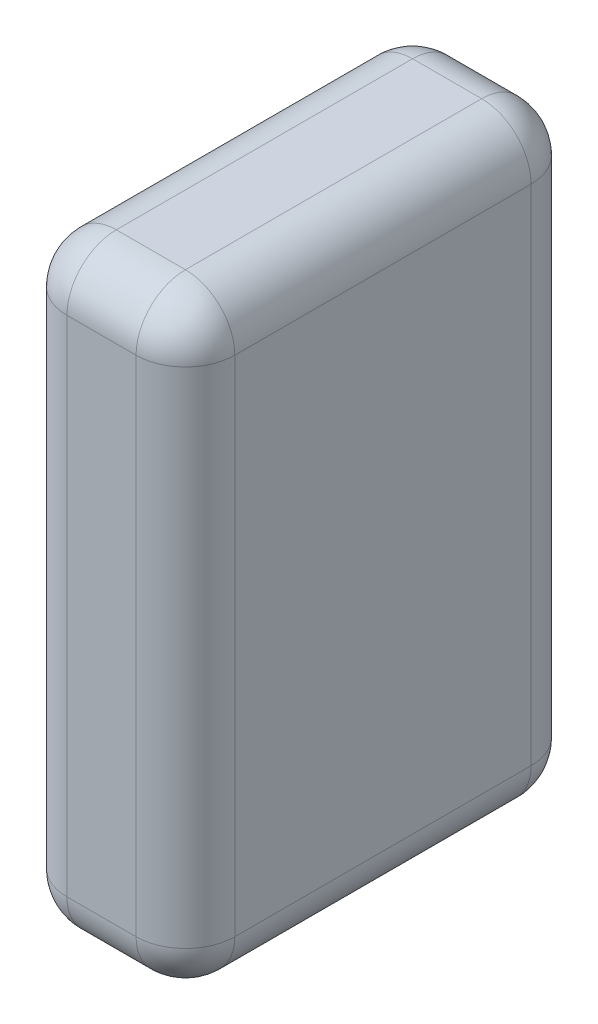
SolidWorks part; units mm, degrees
ref_plane "Front Plane" through (0, 0, 0) normal (0, 0, 1) x (1, 0, 0)
ref_plane "Top Plane" through (0, 0, 0) normal (0, 1, 0) x (1, 0, 0)
ref_plane "Right Plane" through (0, 0, 0) normal (1, 0, 0) x (0, 0, -1)
sketch "xy" plane through (0, 0, 0) normal (0, 0, 1) x (1, 0, 0)
  line L0 (0, 18.1755) -> (0, -18.1755) construction
  line L1 (-29.7176, 0) -> (29.7176, 0) construction
sketch "z" plane through (0, 0, 0) normal (1, 0, 0) x (0, 0, -1)
  line L0 (-17.0064, 0) -> (17.0064, 0) construction
sketch "FrontSketch" plane through (0, 0, 0) normal (0, 0, 1) x (1, 0, 0)
  line L1 (8.5, -30.5) -> (-8.5, -30.5)
  line L2 (8.5, -30.5) -> (8.5, 30.5)
  line L3 (8.5, 30.5) -> (-8.5, 30.5)
  line L4 (-8.5, -30.5) -> (-8.5, 30.5)
  line L5 (8.5, -30.5) -> (-8.5, 30.5) construction
  line L6 (8.5, 30.5) -> (-8.5, -30.5) construction
  point P0 (0, 0)
  dimension "D1" = 61
  dimension "D2" = 17
sketch "RightSketch" plane through (0, 0, 0) normal (1, 0, 0) x (0, 0, -1)
  line L0 (0, 0) -> (-40, 0) construction
  dimension "D1" = 40
extrude "Boss-Extrude1" add sketch "FrontSketch" along normal up to vertex (40 mm away) up to point (0, 0, 40)
fillet "Fillet1" radius 5 12 edges at (-8.5, 0, 0) (0, -30.5, 40) (-8.5, -30.5, 20) (8.5, -30.5, 20) (0, -30.5, 0) (0, 30.5, 0) (8.5, 30.5, 20) (8.5, 0, 0) (8.5, 0, 40) (-8.5, 30.5, 20) (0, 30.5, 40) (-8.5, 0, 40)
